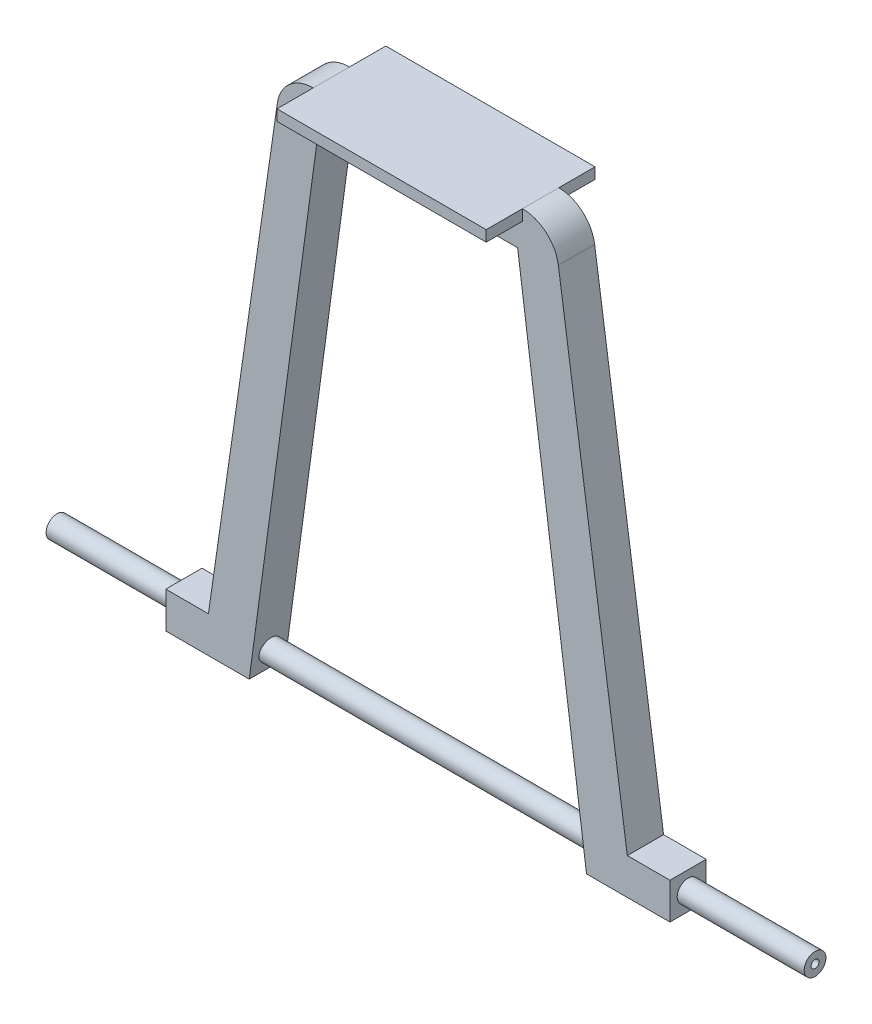
SolidWorks part; units mm, degrees
ref_plane "Front Plane" through (0, 0, 0) normal (0, 0, 1) x (1, 0, 0)
ref_plane "Top Plane" through (0, 0, 0) normal (0, 1, 0) x (1, 0, 0)
ref_plane "Right Plane" through (0, 0, 0) normal (1, 0, 0) x (0, 0, -1)
sketch "Sketch1" plane through (0, 0, 0) normal (0, 0, 1) x (1, 0, 0)
  line L1 (0, 0) -> (55, 0)
  line L2 (0, 0) -> (0, 10)
  line L3 (0, 10) -> (55, 10)
  line L4 (55, 0) -> (55, 10)
  dimension "D1" = 55
  dimension "D2" = 10
extrude "Boss-Extrude1" add sketch "Sketch1" along normal blind 10
sketch "Sketch3" plane through (0, 0, 10) normal (0, 0, 1) x (1, 0, 0)
  line L0 (0, 0) -> (-18.993, -140)
  line L1 (0, 10) -> (-1.3419, 10)
  line L2 (-11.239, 1.431) -> (-31.6884, -140)
  line L3 (-31.6884, -140) -> (-18.993, -140)
  line L4 (0, 10) -> (0, 0) construction
  line L5 (0, 0) -> (55, 0) construction
  line L6 (0, 10) -> (0, 0)
  arc A0 (-11.239, 1.431) -> (-1.3419, 10) centre (-1.3419, 0) cw
  point P14 (-10, 10)
  dimension "D6" = 10
  dimension "D1" = 10
  dimension "D2" = 140
  dimension "D3" = 150
  dimension "D4" = 18.993
  dimension "D5" = 31.6884
extrude "Boss-Extrude2" add sketch "Sketch3" against normal blind 10 contours L2 L3 L0 L6 L1 A0
ref_plane "Plane1" through (27.5, 0, 0) normal (1, 0, 0) x (0, 0, -1)
mirror "Mirror1" about plane through (27.5, 0, 0) normal (1, 0, 0) of "Boss-Extrude2"
ref_plane "Plane2" through (80, 0, 0) normal (1, 0, 0) x (0, 0, -1)
sketch "Sketch6" plane through (80, 0, 0) normal (1, 0, 0) x (0, 0, -1)
  line L0 (0, 1.431) -> (0, -140) construction
  line L1 (-10, -140) -> (0, -140)
  line L2 (-10, -140) -> (-10, -130)
  line L3 (-10, -130) -> (0, -130)
  line L4 (0, -140) -> (0, -130)
  dimension "D1" = 10
extrude "Boss-Extrude3" add sketch "Sketch6" along normal blind 52
mirror "Mirror2" about plane through (27.5, 0, 0) normal (1, 0, 0) of "Boss-Extrude3"
sketch "Sketch7" plane through (0, 10, 0) normal (0, 1, 0) x (1, 0, 0)
  line L0 (-1.3419, 0) -> (-1.3419, -10) construction
  line L1 (-1.3419, 10) -> (56.3419, 10)
  line L2 (-1.3419, 10) -> (-1.3419, -20)
  line L3 (-1.3419, -20) -> (56.3419, -20)
  line L4 (56.3419, 10) -> (56.3419, -20)
  line L5 (-1.3419, 10) -> (56.3419, -20) construction
  line L6 (-1.3419, -20) -> (56.3419, 10) construction
  line L7 (56.3419, 0) -> (56.3419, -10) construction
  line L8 (56.3419, 0) -> (-1.3419, 0) construction
  point P0 (27.5, -5)
  dimension "D1" = 30
  dimension "D2" = 10
extrude "Boss-Extrude4" add sketch "Sketch7" against normal blind 3
sketch "Sketch9" plane through (-77, 0, 0) normal (-1, 0, 0) x (0, 0, 1)
  circle A0 centre (5, -135) radius 3
  dimension "D1" = 6
extrude "Cut-Extrude1" cut sketch "Sketch9" against normal blind 35 flip side to cut
sketch "Sketch10" plane through (132, 0, 0) normal (1, 0, 0) x (0, 0, -1)
  circle A0 centre (-5, -135) radius 3
  dimension "D1" = 6
extrude "Cut-Extrude2" cut sketch "Sketch10" against normal blind 35 flip side to cut
sketch "Sketch13" plane through (97, 0, 0) normal (1, 0, 0) x (0, 0, -1)
  line L0 (-10, -130) -> (-10, -140) construction
  line L1 (0, -130) -> (0, -140) construction
  line L2 (-10, -140) -> (0, -140) construction
  line L3 (0, -130) -> (-10, -130) construction
  line L4 (-10, -130) -> (-10, -140)
  line L5 (0, -130) -> (0, -140)
  line L6 (-10, -140) -> (0, -140)
  line L7 (0, -130) -> (-10, -130)
sketch "Sketch14" plane through (132, 0, 0) normal (1, 0, 0) x (0, 0, -1)
  circle A1 centre (-5, -135) radius 3
  circle A2 centre (-5, -135) radius 3
  dimension "D1" = 0
extrude "Boss-Extrude6" add sketch "Sketch14" against normal up to surface (209 mm away) up to face at (-77, -135, 8)
sketch "Sketch15" plane through (-77, 0, 0) normal (-1, 0, 0) x (0, 0, 1)
  circle A0 centre (5, -135) radius 1.1
  dimension "D1" = 2.2
extrude "Cut-Extrude3" cut sketch "Sketch15" against normal blind 230
